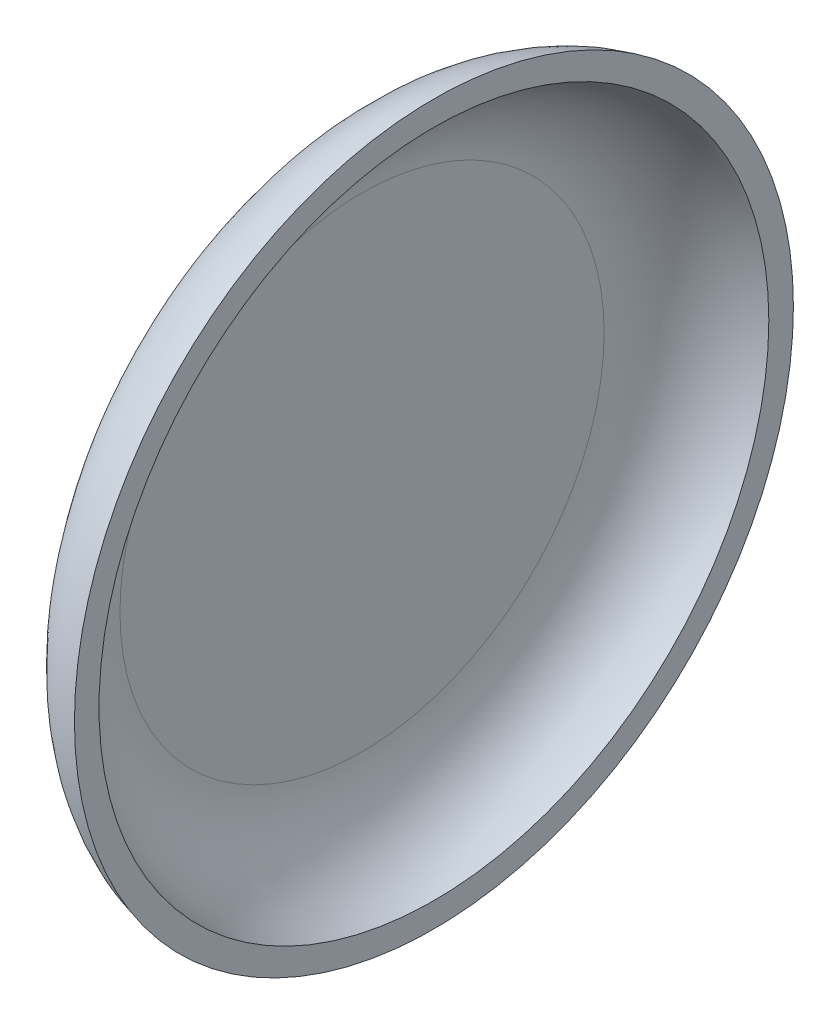
SolidWorks part; units mm, degrees
ref_plane "Ön Düzlem" through (0, 0, 0) normal (0, 0, 1) x (1, 0, 0)
ref_plane "Üst Düzlem" through (0, 0, 0) normal (0, 1, 0) x (1, 0, 0)
ref_plane "Sağ Düzlem" through (0, 0, 0) normal (1, 0, 0) x (0, 0, -1)
sketch "Çizim1" plane through (0, 0, 0) normal (0, 0, 1) x (1, 0, 0)
  line L0 (0, 15) -> (0, 0) construction
  line L1 (0, 0) -> (-12.7611, 0) construction
  line L2 (-4, 0) -> (-4, 10.101)
  line L3 (-3, 0) -> (-3, 10.101)
  line L4 (0, 15) -> (0, 13.974)
  line L5 (-4, 0) -> (-3, 0)
  arc A0 (-4, 10.101) -> (0, 15) centre (1, 10.101) cw
  arc A1 (-3, 10.101) -> (0, 13.974) centre (1, 10.101) cw
  arc A3 (-3, 10.101) -> (0.2, 14.0202) centre (1, 10.101) cw construction
  dimension "D3" = 5
  dimension "D1" = 15
  dimension "D2" = 4
  dimension "D4" = 1
revolve "Döndür1" add sketch "Çizim1" angle 360 about L1
